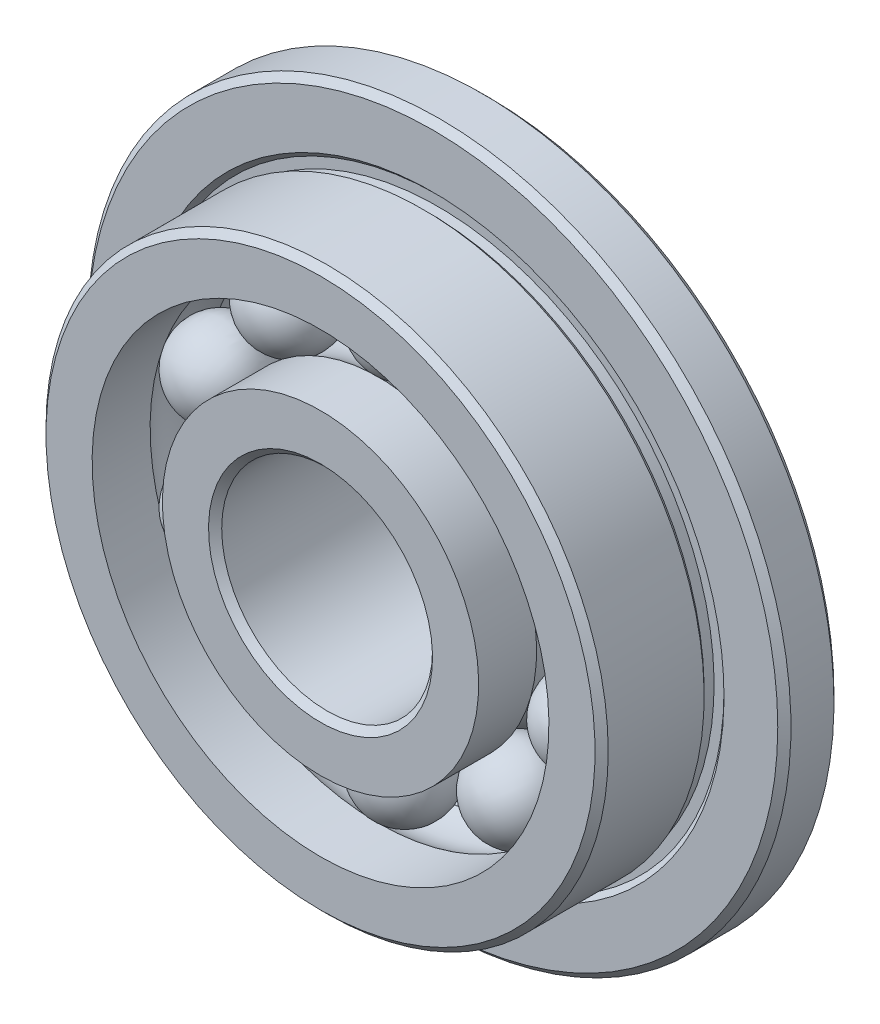
SolidWorks part; units mm, degrees
ref_plane "Front Plane" through (0, 0, 0) normal (0, 0, 1) x (1, 0, 0)
ref_plane "Top Plane" through (0, 0, 0) normal (0, 1, 0) x (1, 0, 0)
ref_plane "Right Plane" through (0, 0, 0) normal (1, 0, 0) x (0, 0, -1)
sketch "Sketch1" plane through (0, 0, 0) normal (1, 0, 0) x (0, 0, -1)
  line L0 (0, 2) -> (0, -2) construction
  line L1 (-0.6, 2) -> (0.6, 2) construction
  line L2 (0, 0) -> (0.6, 0) construction
  line L3 (0.6, 2.5) -> (0.6, -2.5) construction
  line L4 (0.6, -2.5) -> (0.2, -2.5) construction
  line L5 (0.6, 0.75) -> (0, 0.75) construction
  line L6 (0.6, 0.75) -> (0.6, -0.75) construction
  dimension "OD" = 4
  dimension "Width" = 1.2
  dimension "Flange Thickness" = 0.4
  dimension "ID" = 1.5
  dimension "Flange OD" = 5
sketch "Sketch2" plane through (0, 0, 0) normal (1, 0, 0) x (0, 0, -1)
  line L0 (0.6, 2.5) -> (0.2, 2.5)
  line L1 (0.2, 2.5) -> (0.2, 2.0707)
  line L2 (0.1293, 2) -> (-0.6, 2)
  line L3 (-0.6, 2) -> (-0.6, 1.625)
  line L4 (-0.6, 1.625) -> (-0.1875, 1.625)
  line L5 (0.6, 2.5) -> (0.6, -2.5) construction
  line L6 (0.6, 1.625) -> (0.6, 2.5)
  line L7 (0.6, 0.75) -> (-0.6, 0.75)
  line L8 (-0.6, 0.75) -> (-0.6, 1.125)
  line L9 (-0.6, 1.125) -> (-0.1875, 1.125)
  line L10 (0.6, 1.125) -> (0.6, 0.75)
  line L11 (0, 2) -> (0, 0.75) construction
  line L12 (-0.3125, 1.375) -> (0.3125, 1.375) construction
  line L13 (0.1875, 1.625) -> (0.6, 1.625)
  line L14 (0.1875, 1.125) -> (0.6, 1.125)
  line L15 (0.2, 2.0707) -> (0.2354, 2.0354)
  line L16 (0.2354, 2.0354) -> (0.2354, 1.9646)
  line L17 (0.2354, 1.9646) -> (0.1646, 1.9646)
  line L18 (0.1646, 1.9646) -> (0.1293, 2)
  line L19 (0.2, 2) -> (0.2354, 1.9646) construction
  line L20 (0.2354, 2.0354) -> (0.1646, 1.9646) construction
  line L21 (0.1293, 2) -> (0.2, 2) construction
  line L22 (0.2, 2) -> (0.2, 2.0707) construction
  circle A0 centre (0, 1.375) radius 0.3125 construction
  arc A1 (-0.1875, 1.625) -> (0.1875, 1.625) centre (0, 1.375) cw
  arc A2 (-0.1875, 1.125) -> (0.1875, 1.125) centre (0, 1.375) ccw
  dimension "D1" = 1.25
  dimension "Ball Dia." = 0.625
  dimension "D2" = 135
  dimension "D3" = 0.1
  dimension "D4" = 0.5
  dimension "Race Thikness" = 0.375
revolve "Revolve1" add sketch "Sketch2" angle 360 about L2
fillet "Fillet1" radius 0.0469 3 edges at (0, -2.5, -0.6) (0, -2.5, -0.2) (0, -2, 0.6) profile chamfer
sketch "Sketch3" plane through (0, 0, 0) normal (0, 0, 1) x (1, 0, 0)
  line L0 (-0.75, 0) -> (0.75, 0) construction
  line L1 (-2, 0) -> (2, 0) construction
  point P5 (0, 0)
  dimension "ID2" = 1.5
  dimension "OD2" = 4
fillet "Fillet2" radius 0.0469 2 edges at (0, -0.75, -0.6) (0, -0.75, 0.6) profile chamfer
sketch "Sketch7" plane through (0, 0, 0) normal (0, 0, 1) x (1, 0, 0)
  line L0 (0, 1.6875) -> (0, 1.0625)
  line L1 (0, 2.5) -> (0, -2.5) construction
  line L2 (-0.3938, 1.6875) -> (0, 0) construction
  line L3 (0, 0) -> (0.3938, 1.6875) construction
  line L4 (0.3938, 1.6875) -> (-0.3938, 1.6875) construction
  circle A0 centre (0, 1.375) radius 0.3125 construction
  circle A1 centre (0, 0) radius 1.6875 construction
  circle A2 centre (0, 0) radius 1.0625 construction
  arc A4 (0, 1.6875) -> (0, 1.0625) centre (0, 1.375) ccw
  dimension "D1" = 26.273
revolve "Revolve3" add sketch "Sketch7" angle 360 about L0
pattern_circular "CirPattern3" count 10 over 360 about axis through (0, 0, 0) along (0, 0, 1) of bodies 107
sketch "Sketch8" plane through (0, 0, 0) normal (1, 0, 0) x (0, 0, -1)
  line L0 (-0.6, 2) -> (0.6, 2) construction
  line L1 (0.6, 2) -> (0.6, 2.5) construction
  line L2 (-0.6, -2) -> (0.6, -2) construction
  line L3 (0.6, 2.5) -> (0.6, -2.5) construction
  dimension "D1" = 4
equation "\"Ball Dia.@Sketch2\" = ( \"OD@Sketch1\" - \"ID@Sketch1\" ) * .25"
equation "\"D3@Sketch2\"=\"Flange Thickness@Sketch1\"/4"
equation "\"D1@Fillet1\" = \"Race Thikness@Sketch2\" / 8"
equation "\"ID2@Sketch3\" = \"ID@Sketch1\""
equation "\"OD2@Sketch3\" = \"OD@Sketch1\""
equation "\"D1@Fillet2\" = \"Race Thikness@Sketch2\" / 8"
equation "\"D1@CirPattern3\"=360/\"D1@Sketch7\"-4"
equation "\"D4@Sketch2\" = ( \"OD@Sketch1\" - \"ID@Sketch1\" ) * .2"
